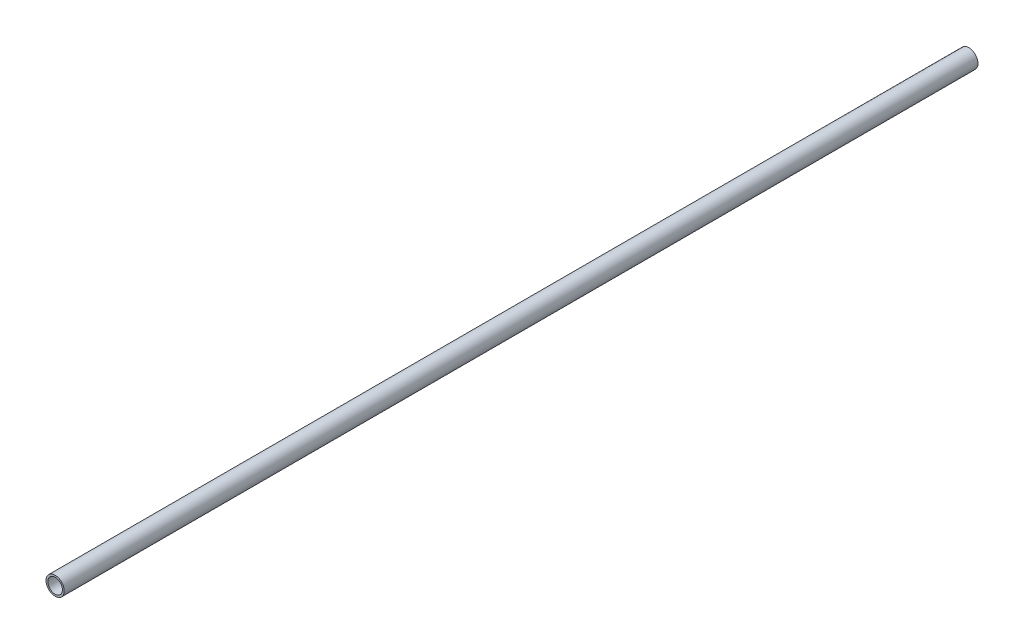
SolidWorks part; units mm, degrees
ref_plane "Płaszczyzna przednia" through (0, 0, 0) normal (0, 0, 1) x (1, 0, 0)
ref_plane "Płaszczyzna górna" through (0, 0, 0) normal (0, 1, 0) x (1, 0, 0)
ref_plane "Płaszczyzna prawa" through (0, 0, 0) normal (1, 0, 0) x (0, 0, -1)
sketch "Szkic1" plane through (0, 0, 0) normal (0, 0, 1) x (1, 0, 0)
  circle A0 centre (0, 0) radius 5
extrude "Dodanie-wyciągnięcie1" add sketch "Szkic1" along normal blind 500
sketch "Szkic2" plane through (0, 0, 500) normal (0, 0, 1) x (1, 0, 0)
  circle A0 centre (0, 0) radius 4
extrude "Wytnij-wyciągnięcie1" cut sketch "Szkic2" against normal blind 500
